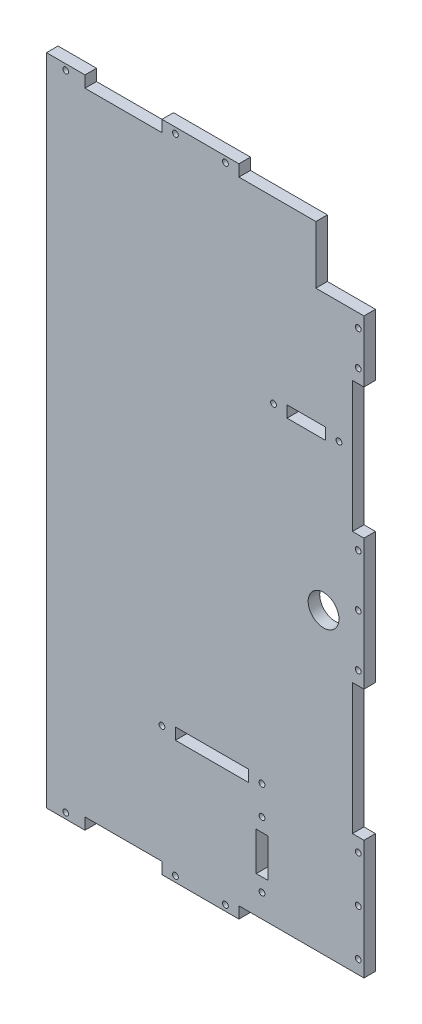
SolidWorks part; units mm, degrees
ref_plane "Plan de face" through (0, 0, 0) normal (0, 0, 1) x (1, 0, 0)
ref_plane "Plan de dessus" through (0, 0, 0) normal (0, 1, 0) x (1, 0, 0)
ref_plane "Plan de droite" through (0, 0, 0) normal (1, 0, 0) x (0, 0, -1)
sketch "Esquisse2" plane through (0, 0, 0) normal (0, 0, 1) x (1, 0, 0)
  line L1 (0, 0) -> (-330, 0)
  line L2 (0, 0) -> (0, -340)
  line L3 (0, -340) -> (-330, -340)
  line L4 (-330, 0) -> (-330, -340)
  dimension "D1" = 340
  dimension "D2" = 330
extrude "Boss.-Extru.1" add sketch "Esquisse2" along normal blind 6
sketch "Esquisse4" plane through (0, 0, 0) normal (0, 0, -1) x (-1, 0, 0)
  line L0 (0, 0) -> (330, 0) construction
  line L1 (330, 0) -> (265, 0)
  line L2 (330, 0) -> (330, -6)
  line L3 (330, -6) -> (265, -6)
  line L4 (265, 0) -> (265, -6)
  line L5 (225, 0) -> (185, 0)
  line L6 (225, 0) -> (225, -6)
  line L7 (225, -6) -> (185, -6)
  line L8 (185, 0) -> (185, -6)
  line L9 (330, 0) -> (330, -340) construction
  line L10 (145, 0) -> (105, 0)
  line L11 (145, 0) -> (145, -6)
  line L12 (145, -6) -> (105, -6)
  line L13 (105, 0) -> (105, -6)
  line L14 (0, 0) -> (65, 0)
  line L15 (0, 0) -> (0, -6)
  line L16 (0, -6) -> (65, -6)
  line L17 (65, 0) -> (65, -6)
  line L19 (330, -68) -> (324, -68)
  line L20 (330, -68) -> (330, -136)
  line L21 (330, -136) -> (324, -136)
  line L22 (330, -340) -> (0, -340) construction
  line L23 (324, -68) -> (324, -136)
  line L24 (0, -136) -> (6, -136)
  line L25 (0, -136) -> (0, -68)
  line L26 (0, -68) -> (6, -68)
  line L27 (330, -340) -> (265, -340)
  line L28 (330, -340) -> (330, -334)
  line L29 (330, -334) -> (265, -334)
  line L30 (265, -340) -> (265, -334)
  line L31 (225, -340) -> (185, -340)
  line L32 (225, -340) -> (225, -334)
  line L33 (225, -334) -> (185, -334)
  line L34 (185, -340) -> (185, -334)
  line L35 (0, -340) -> (0, 0) construction
  line L36 (145, -340) -> (105, -340)
  line L37 (145, -340) -> (145, -334)
  line L38 (145, -334) -> (105, -334)
  line L39 (105, -340) -> (105, -334)
  line L40 (65, -340) -> (0, -340)
  line L41 (65, -340) -> (65, -334)
  line L42 (65, -334) -> (0, -334)
  line L43 (0, -340) -> (0, -334)
  line L44 (330, -204) -> (324, -204)
  line L45 (330, -204) -> (330, -272)
  line L46 (330, -272) -> (324, -272)
  line L47 (324, -204) -> (324, -272)
  line L48 (6, -136) -> (6, -68)
  line L52 (0, -204) -> (6, -204)
  line L53 (0, -204) -> (0, -272)
  line L54 (0, -272) -> (6, -272)
  line L55 (6, -204) -> (6, -272)
  dimension "D1" = 6
  dimension "D2" = 65
  dimension "D3" = 40
  dimension "D4" = 6
  dimension "D5" = 40
  dimension "D6" = 40
  dimension "D7" = 6
  dimension "D8" = 40
  dimension "D9" = 40
  dimension "D10" = 6
  dimension "D11" = 68
  dimension "D12" = 6
  dimension "D13" = 68
  dimension "D14" = 68
  dimension "D15" = 65
  dimension "D16" = 6
  dimension "D17" = 6
  dimension "D18" = 40
  dimension "D19" = 40
  dimension "D20" = 40
  dimension "D21" = 40
  dimension "D22" = 6
  dimension "D23" = 65
  dimension "D24" = 40
  dimension "D25" = 6
  dimension "D26" = 68
  dimension "D27" = 68
  dimension "D28" = 68
  dimension "D29" = 68
  dimension "D30" = 6
  dimension "D31" = 6
  dimension "D32" = 68
  dimension "D34" = 6
extrude "Enlèv. mat encoche bord" cut sketch "Esquisse4" against normal through all
sketch "Esquisse5" plane through (0, 0, 0) normal (0, 0, -1) x (-1, 0, 0)
  line L0 (265, -340) -> (225, -340) construction
  line L1 (270, -276) -> (232, -276)
  line L2 (270, -276) -> (270, -270)
  line L3 (270, -270) -> (232, -270)
  line L4 (232, -276) -> (232, -270)
  line L5 (98, -276) -> (60, -276)
  line L6 (98, -276) -> (98, -270)
  line L7 (98, -270) -> (60, -270)
  line L8 (60, -276) -> (60, -270)
  line L9 (330, -6) -> (315, -6)
  line L10 (330, -6) -> (330, -16)
  line L11 (330, -16) -> (315, -16)
  line L12 (315, -6) -> (315, -16)
  line L13 (0, -6) -> (25, -6)
  line L14 (0, -6) -> (0, -36)
  line L15 (0, -36) -> (25, -36)
  line L16 (25, -6) -> (25, -36)
  line L17 (310, -102) -> (290, -102)
  line L19 (0, -68) -> (0, -6) construction
  line L20 (330, -272) -> (330, -334) construction
  line L21 (310, -102) -> (310, -96)
  line L22 (310, -96) -> (290, -96)
  line L23 (290, -102) -> (290, -96)
  line L24 (40, -102) -> (20, -102)
  line L25 (40, -102) -> (40, -96)
  line L26 (40, -96) -> (20, -96)
  line L27 (20, -102) -> (20, -96)
  line L28 (50, -315) -> (56, -315)
  line L29 (50, -315) -> (50, -295)
  line L30 (105, -340) -> (65, -340) construction
  line L31 (225, 0) -> (265, 0) construction
  line L32 (65, 0) -> (105, 0) construction
  line L33 (50, -295) -> (56, -295)
  line L34 (56, -315) -> (56, -295)
  line L35 (0, -334) -> (0, -272) construction
  line L36 (105, -340) -> (65, -340) construction
  dimension "D1" = 6
  dimension "D2" = 38
  dimension "D3" = 38
  dimension "D4" = 6
  dimension "D5" = 134
  dimension "D6" = 60
  dimension "D7" = 10
  dimension "D8" = 70
  dimension "D9" = 102
  dimension "D10" = 15
  dimension "D11" = 30
  dimension "D12" = 25
  dimension "D13" = 20
  dimension "D14" = 102
  dimension "D15" = 6
  dimension "D16" = 6
  dimension "D17" = 20
  dimension "D18" = 70
  dimension "D19" = 20
  dimension "D20" = 20
  dimension "D21" = 20
  dimension "D22" = 25
  dimension "D23" = 50
  dimension "D24" = 6
extrude "Enlèv. mat encoche étage + roulettes" cut sketch "Esquisse5" against normal through all
sketch "Esquisse6" plane through (0, 0, 6) normal (0, 0, 1) x (1, 0, 0)
  line L0 (-105, -340) -> (-65, -340) construction
  line L1 (0, -204) -> (0, -136) construction
  line L2 (-330, -136) -> (-330, -204) construction
  line L3 (-265, -340) -> (-225, -340) construction
  circle A0 centre (-21, -178.92) radius 8
  circle A1 centre (-309, -178.92) radius 8
  dimension "D3" = 16
  dimension "D4" = 16
  dimension "D1" = 161.08
  dimension "D2" = 21
  dimension "D5" = 21
  dimension "D6" = 161.08
extrude "Enlèv. mat.-Extru.1" cut sketch "Esquisse6" against normal blind 10
sketch "Esquisse7" plane through (0, 0, 6) normal (0, 0, 1) x (1, 0, 0)
  line L0 (-145, 0) -> (-185, 0) construction
  line L1 (-165, 0) -> (-335.3182, 0)
  line L2 (-165, 0) -> (-165, -348.0322)
  line L3 (-165, -348.0322) -> (-335.3182, -348.0322)
  line L4 (-335.3182, 0) -> (-335.3182, -348.0322)
extrude "Enlèv. mat.-Extru.2" cut sketch "Esquisse7" against normal through all
sketch "Esquisse8" plane through (0, 0, 0) normal (0, 0, -1) x (-1, 0, 0)
  line L0 (165, -340) -> (145, -340) construction
  line L1 (145, -340) -> (145, -334) construction
  line L2 (105, -340) -> (65, -340) construction
  line L3 (105, -334) -> (105, -340) construction
  line L4 (65, -340) -> (65, -334) construction
  line L5 (50, -315) -> (56, -315) construction
  line L6 (56, -315) -> (56, -295) construction
  line L7 (56, -295) -> (50, -295) construction
  line L8 (60, -270) -> (60, -276) construction
  line L9 (98, -270) -> (60, -270) construction
  line L10 (98, -276) -> (98, -270) construction
  line L11 (65, -334) -> (0, -334) construction
  line L12 (0, -334) -> (0, -272) construction
  line L13 (0, -272) -> (6, -272) construction
  line L14 (0, -204) -> (0, -136) construction
  line L15 (6, -204) -> (0, -204) construction
  line L16 (0, -136) -> (6, -136) construction
  line L17 (145, 0) -> (165, 0) construction
  line L18 (145, -6) -> (145, 0) construction
  line L19 (105, -6) -> (145, -6) construction
  line L20 (105, 0) -> (105, -6) construction
  line L21 (65, 0) -> (105, 0) construction
  line L22 (65, -6) -> (65, 0) construction
  line L23 (0, -68) -> (0, -36) construction
  line L24 (6, -68) -> (0, -68) construction
  line L25 (0, -36) -> (25, -36) construction
  line L26 (40, -102) -> (40, -96) construction
  line L27 (20, -102) -> (40, -102) construction
  line L28 (20, -96) -> (20, -102) construction
  circle A0 centre (155, -337) radius 1.5
  circle A1 centre (98, -337) radius 1.5
  circle A2 centre (72, -337) radius 1.5
  circle A3 centre (3, -327) radius 1.5
  circle A4 centre (3, -303) radius 1.5
  circle A5 centre (3, -279) radius 1.5
  circle A6 centre (53, -288) radius 1.5
  circle A7 centre (53, -322) radius 1.5
  circle A8 centre (53, -273) radius 1.5
  circle A9 centre (105, -273) radius 1.5
  circle A10 centre (3, -197) radius 1.5
  circle A11 centre (3, -170) radius 1.5
  circle A12 centre (3, -143) radius 1.5
  circle A13 centre (3, -61) radius 1.5
  circle A14 centre (3, -43) radius 1.5
  circle A15 centre (98, -3) radius 1.5
  circle A16 centre (72, -3) radius 1.5
  circle A17 centre (155, -3) radius 1.5
  circle A18 centre (47, -99) radius 1.5
  circle A19 centre (13, -99) radius 1.5
  point P56 (60, -273)
  point P67 (3, -272)
  point P72 (3, -204)
  point P83 (105, -3)
  point P100 (20, -99)
  dimension "D1" = 3
  dimension "D2" = 3
  dimension "D3" = 10
  dimension "D4" = 3
  dimension "D5" = 3
  dimension "D6" = 7
  dimension "D7" = 3
  dimension "D8" = 3
  dimension "D9" = 7
  dimension "D10" = 3
  dimension "D11" = 7
  dimension "D12" = 3
  dimension "D13" = 3
  dimension "D14" = 7
  dimension "D15" = 3
  dimension "D16" = 3
  dimension "D17" = 7
  dimension "D18" = 3
  dimension "D19" = 3
  dimension "D20" = 7
  dimension "D21" = 3
  dimension "D22" = 3
  dimension "D23" = 7
  dimension "D24" = 3
  dimension "D25" = 3
  dimension "D27" = 31
  dimension "D28" = 3
  dimension "D29" = 3
  dimension "D30" = 7
  dimension "D31" = 3
  dimension "D32" = 3
  dimension "D33" = 7
  dimension "D34" = 3
  dimension "D36" = 34
  dimension "D37" = 3
  dimension "D39" = 7
  dimension "D40" = 3
  dimension "D42" = 10
  dimension "D43" = 3
  dimension "D44" = 3
  dimension "D46" = 3
  dimension "D48" = 7
  dimension "D49" = 3
  dimension "D50" = 3
  dimension "D51" = 7
  dimension "D52" = 3
  dimension "D54" = 3
  dimension "D55" = 3
  dimension "D57" = 3
  dimension "D58" = 3
  dimension "D60" = 3
  dimension "D26" = 3
  dimension "D35" = 3
  dimension "D38" = 3
  dimension "D41" = 3
  dimension "D45" = 7
  dimension "D47" = 3
  dimension "D53" = 7
  dimension "D56" = 7
  dimension "D59" = 7
extrude "Enlèv. mat.-Extru.3" cut sketch "Esquisse8" against normal through all
sketch "Esquisse9" plane through (0, 0, 0) normal (0, 0, -1) x (-1, 0, 0)
  circle A0 centre (155, -337) radius 2.995
  circle A1 centre (98, -337) radius 2.995
  circle A3 centre (72, -337) radius 2.995
  circle A4 centre (53, -322) radius 3
  circle A5 centre (53, -288) radius 2.995
  circle A7 centre (53, -273) radius 2.995
  circle A8 centre (105, -273) radius 2.995
  circle A9 centre (3, -279) radius 2.995
  circle A10 centre (3, -303) radius 2.995
  circle A11 centre (3, -327) radius 2.995
  circle A12 centre (3, -197) radius 2.995
  circle A13 centre (3, -170) radius 2.995
  circle A14 centre (3, -143) radius 2.995
  circle A15 centre (47, -99) radius 3
  circle A16 centre (13, -99) radius 3
  circle A17 centre (3, -61) radius 2.995
  circle A18 centre (3, -43) radius 2.995
  circle A19 centre (98, -3) radius 2.995
  circle A20 centre (72, -3) radius 2.995
  circle A21 centre (155, -3) radius 2.995
  dimension "D1" = 5.99
  dimension "D2" = 5.99
  dimension "D3" = 5.99
  dimension "D4" = 6
  dimension "D5" = 5.99
  dimension "D6" = 5.99
  dimension "D7" = 5.99
  dimension "D8" = 5.99
  dimension "D9" = 5.99
  dimension "D10" = 5.99
  dimension "D11" = 5.99
  dimension "D12" = 5.99
  dimension "D13" = 5.99
  dimension "D14" = 6
  dimension "D15" = 6
  dimension "D16" = 5.99
  dimension "D17" = 5.99
  dimension "D18" = 5.99
  dimension "D19" = 5.99
  dimension "D20" = 5.99
extrude "Enlèv. mat.-Extru.4" cut sketch "Esquisse9" against normal blind 3
